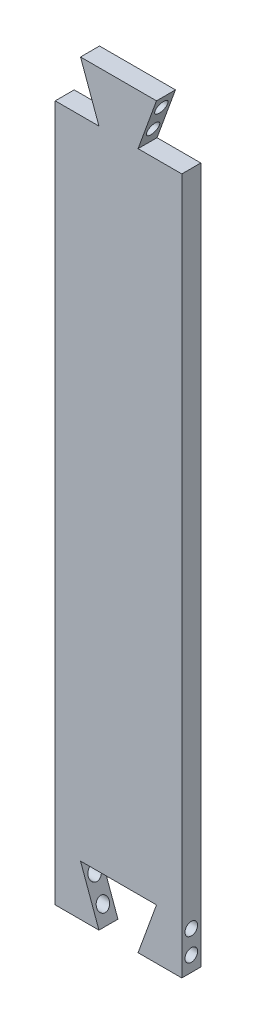
SolidWorks part; units mm, degrees
ref_plane "Front Plane" through (0, 0, 0) normal (0, 0, 1) x (1, 0, 0)
ref_plane "Top Plane" through (0, 0, 0) normal (0, 1, 0) x (1, 0, 0)
ref_plane "Right Plane" through (0, 0, 0) normal (1, 0, 0) x (0, 0, -1)
sketch "Sketch1" plane through (0, 0, 0) normal (0, 0, 1) x (1, 0, 0)
  line L1 (0, 0) -> (50, 0)
  line L2 (0, 0) -> (0, -275)
  line L3 (0, -275) -> (50, -275)
  line L4 (50, 0) -> (50, -275)
  dimension "D1" = 50
  dimension "D2" = 275
extrude "Boss-Extrude1" add sketch "Sketch1" along normal blind 7.5
sketch "Sketch2" plane through (0, 0, 7.5) normal (0, 0, 1) x (1, 0, 0)
  line L0 (17.2794, 0) -> (10, 20)
  line L1 (50, 0) -> (0, 0) construction
  line L2 (10, 20) -> (40, 20)
  line L3 (40, 20) -> (32.7206, 0)
  line L4 (17.2794, 0) -> (32.7206, 0)
  line L5 (17.2794, -1000) -> (17.2794, 49000) construction
  line L6 (32.7206, -1000) -> (32.7206, 49000) construction
  line L7 (25, -980) -> (25, 49020) construction
  point P11 (-6.4704, 0)
  point P13 (25, 20)
  point P14 (25, 0)
  dimension "D1" = 20
  dimension "D2" = 20
  dimension "D3" = 30
  dimension "D4" = 20
extrude "Boss-Extrude2" add sketch "Sketch2" against normal up to surface (7.5 mm away) up to face at (25, -137.5, 0)
sketch "Sketch3" plane through (0, 0, 0) normal (-1, 0, 0) x (0, 0, 1)
  line L1 (0, 20) -> (3.75, 15) construction
  line L2 (3.75, 15) -> (7.5, 20) construction
  line L3 (0, 0) -> (7.5, 0) construction
  circle A0 centre (3.75, 15) radius 2.5
  circle A1 centre (3.75, 6) radius 2.5
  dimension "D3" = 5
  dimension "D1" = 9
  dimension "D2" = 6
extrude "Cut-Extrude1" cut sketch "Sketch3" against normal through all
sketch "Sketch4" plane through (0, 0, 7.5) normal (0, 0, 1) x (1, 0, 0)
  line L0 (17.2794, -275) -> (10, -255)
  line L1 (0, -275) -> (50, -275) construction
  line L2 (10, -255) -> (40, -255)
  line L3 (40, -255) -> (32.7206, -275)
  line L4 (32.7206, -275) -> (17.2794, -275)
  line L5 (17.2794, -1275) -> (17.2794, 48725) construction
  line L6 (32.7206, -1275) -> (32.7206, 48725) construction
  line L7 (25, -1255) -> (25, 48745) construction
  point P11 (-16.3288, -255)
  point P13 (25, -255)
  point P14 (25, -275)
  dimension "D1" = 20
  dimension "D2" = 20
  dimension "D3" = 30
extrude "Cut-Extrude2" cut sketch "Sketch4" against normal up to next
sketch "Sketch5" plane through (0, 0, 0) normal (-1, 0, 0) x (0, 0, 1)
  line L0 (7.5, -275) -> (0, -275) construction
  line L1 (3.75, -269) -> (0, -275) construction
  line L2 (3.75, -269) -> (7.5, -275) construction
  circle A0 centre (3.75, -269) radius 2.5
  circle A1 centre (3.75, -260) radius 2.5
  dimension "D2" = 9
  dimension "D3" = 5
  dimension "D1" = 6
extrude "Cut-Extrude3" cut sketch "Sketch5" against normal through all and the other way through all
